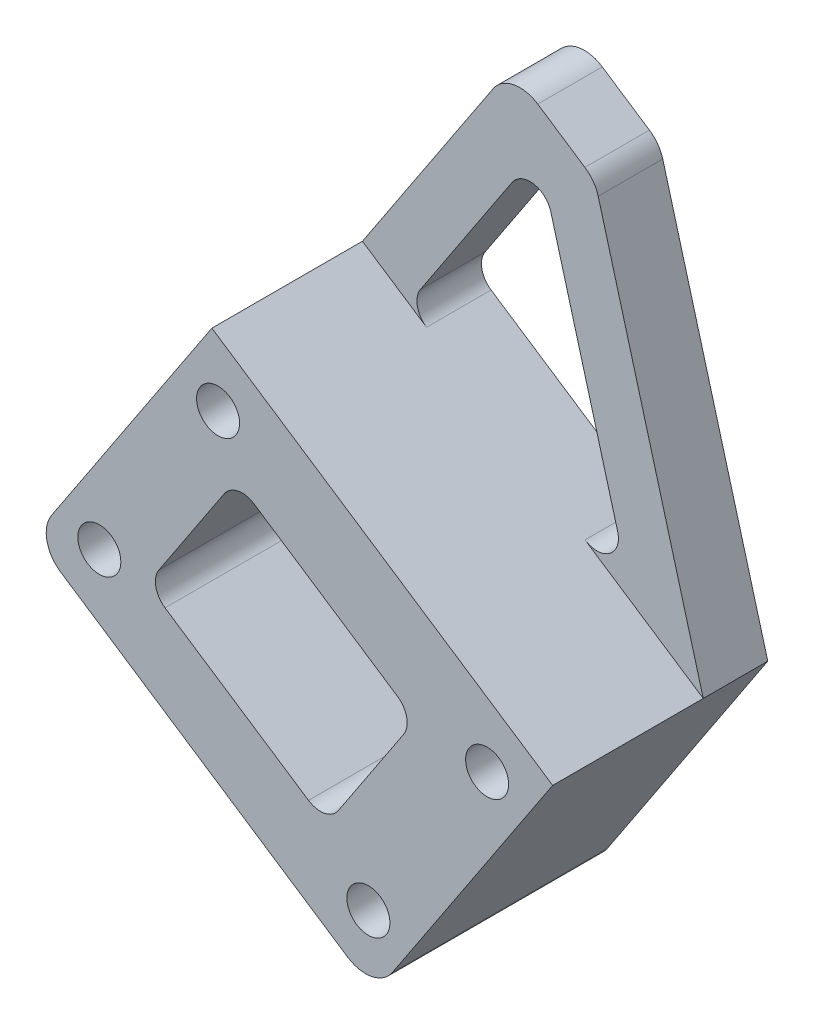
SolidWorks part; units mm, degrees
material "PVC 僵硬"
ref_plane "前视基准面" through (0, 0, 0) normal (0, 0, 1) x (1, 0, 0)
ref_plane "上视基准面" through (0, 0, 0) normal (0, 1, 0) x (1, 0, 0)
ref_plane "右视基准面" through (0, 0, 0) normal (1, 0, 0) x (0, 0, -1)
other "Configuration Table"
sketch "草图1" plane through (0, 0, 0) normal (0, 0, 1) x (1, 0, 0)
  line L0 (8.6419, -30.917) -> (23.5442, -8.4021)
  line L1 (23.5442, -8.4021) -> (13.7775, 27.1541)
  line L2 (12.5405, 28.8612) -> (8.1566, 31.7629)
  line L3 (3.9991, 30.917) -> (-23.0458, -9.9434)
  line L4 (-22.2, -14.1009) -> (4.4844, -31.7629)
  line L5 (3.6146, -20.3943) -> (9.6859, -11.2216)
  line L6 (-12.4992, -12.1272) -> (0.843, -20.9582)
  line L7 (-6.9918, -0.1828) -> (-13.0631, -9.3556)
  line L8 (9.122, -8.4499) -> (-4.2201, 0.3811)
  line L9 (-2.1814, 8.6253) -> (12.554, -1.1278)
  line L10 (5.7751, 24.2699) -> (-2.7453, 11.3969)
  line L11 (15.5864, 1.0697) -> (9.3715, 23.6957)
  circle A0 centre (6.4102, -27.0415) radius 2
  arc A1 (13.7775, 27.1541) -> (12.5405, 28.8612) centre (10.8847, 26.3595) ccw
  arc A2 (8.1566, 31.7629) -> (3.9991, 30.917) centre (6.5008, 29.2612) ccw
  arc A3 (-23.0458, -9.9434) -> (-22.2, -14.1009) centre (-20.5442, -11.5992) ccw
  arc A4 (4.4844, -31.7629) -> (8.6419, -30.917) centre (6.1402, -29.2612) ccw
  circle A5 centre (17.4489, -10.3638) radius 2
  circle A6 centre (-18.6064, -10.4834) radius 2
  circle A7 centre (-7.5677, 6.1943) radius 2
  arc A8 (9.6859, -11.2216) -> (9.122, -8.4499) centre (8.0182, -10.1177) ccw
  arc A9 (0.843, -20.9582) -> (3.6146, -20.3943) centre (1.9468, -19.2904) ccw
  arc A10 (-13.0631, -9.3556) -> (-12.4992, -12.1272) centre (-11.3953, -10.4595) ccw
  arc A11 (-4.2201, 0.3811) -> (-6.9918, -0.1828) centre (-5.324, -1.2867) ccw
  arc A12 (12.554, -1.1278) -> (15.5864, 1.0697) centre (13.6578, 0.5399) ccw
  arc A13 (-2.7453, 11.3969) -> (-2.1814, 8.6253) centre (-1.0775, 10.2931) ccw
  arc A14 (9.3715, 23.6957) -> (5.7751, 24.2699) centre (7.4429, 23.166) ccw
extrude "凸台-拉伸1" add sketch "草图1" along normal blind 20
sketch "草图2" plane through (0, 0, 20) normal (0, 0, 1) x (1, 0, 0)
  line L0 (23.5442, -8.4021) -> (-8.1435, 12.5715)
  line L1 (3.9991, 30.917) -> (-23.0458, -9.9434) construction
  line L5 (-8.1435, 12.5715) -> (4.7024, 35.5619)
  line L6 (4.7024, 35.5619) -> (37.1917, 19.1569)
  line L7 (37.1917, 19.1569) -> (23.5442, -8.4021)
extrude "切除-拉伸2" cut sketch "草图2" against normal blind 14
